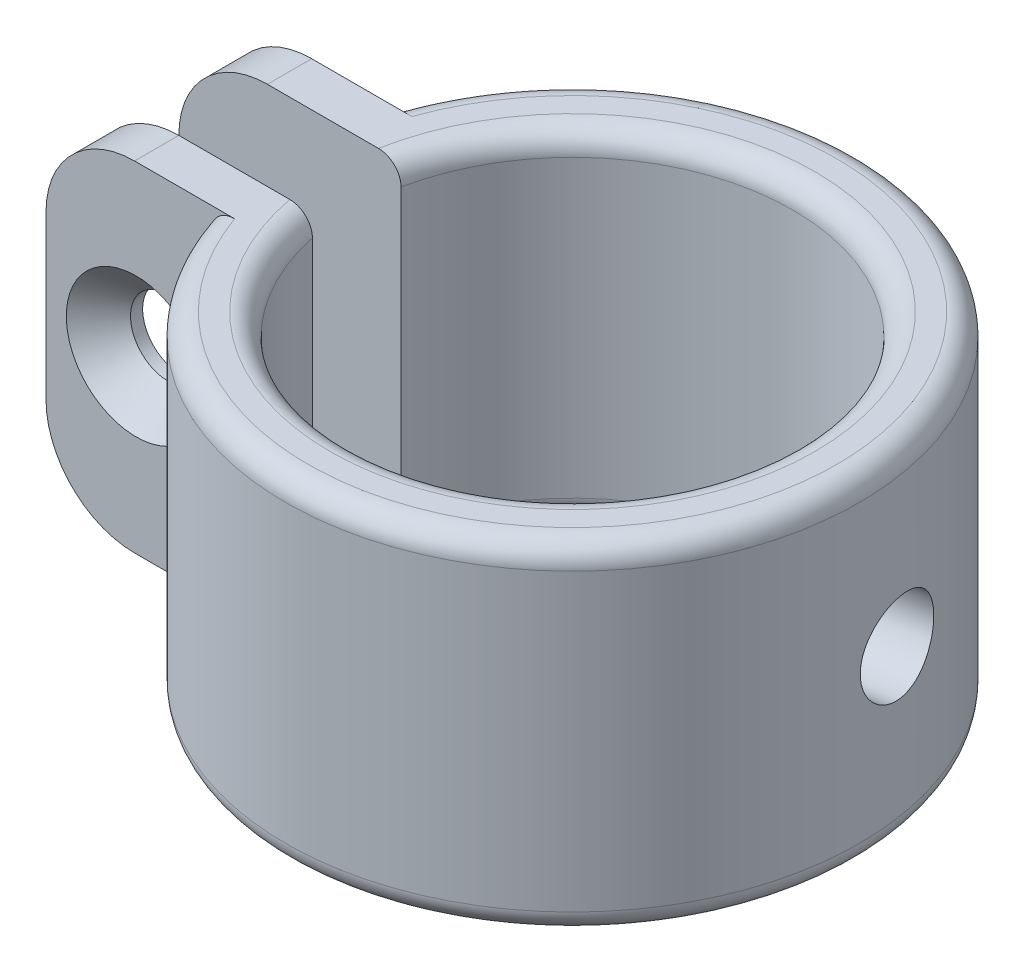
SolidWorks part; units mm, degrees
ref_plane "Front Plane" through (0, 0, 0) normal (0, 0, 1) x (1, 0, 0)
ref_plane "Top Plane" through (0, 0, 0) normal (0, 1, 0) x (1, 0, 0)
ref_plane "Right Plane" through (0, 0, 0) normal (1, 0, 0) x (0, 0, -1)
sketch "Sketch1" plane through (0, 0, 0) normal (0, 0, 1) x (1, 0, 0)
  line L0 (0, 0) -> (0, 130) construction
  line L1 (-9.95, 130) -> (9.95, 130) construction
  line L2 (-3.8, 7) -> (3.8, 7) construction
  line L3 (-3.8, 12.6) -> (3.8, 12.6) construction
  line L4 (-8.875, 30) -> (8.875, 30) construction
  line L5 (-7.05, 21) -> (7.05, 21) construction
  line L6 (-7.6, 30) -> (7.6, 30) construction
  line L7 (3.8, 7) -> (2.8, 7) construction
  line L8 (3.8, 7) -> (3.8, 12.6) construction
  line L9 (3.8, 12.6) -> (7.05, 21) construction
  line L10 (7.05, 21) -> (7.6, 30) construction
  line L11 (7.6, 30) -> (8.875, 30) construction
  line L12 (-9.95, 129.5) -> (9.95, 129.5) construction
  line L13 (8.875, 30) -> (9.95, 129.5) construction
  line L14 (9.95, 129.5) -> (9.95, 29.121) construction
  line L15 (9.95, 52.2759) -> (12.95, 52.2759)
  line L16 (9.95, 52.2759) -> (9.95, 36.9424)
  line L17 (9.95, 36.9424) -> (12.95, 36.9424)
  line L18 (12.95, 52.2759) -> (12.95, 36.9424)
  line L19 (9.95, 52.2759) -> (12.95, 36.9424) construction
  line L20 (9.95, 36.9424) -> (12.95, 52.2759) construction
  spline S0 degree 2 poles (0, 0) (0.935, 0.0329) (2.8, 7) knots 0 0 0 1 1 1 construction
  spline S1 degree 2 poles (0, 130) (7.4447, 130.0874) (9.95, 129.5) knots 0 0 0 1 1 1 construction
  point P4 (0, 130)
  point P7 (0, 7)
  point P10 (0, 12.6)
  point P13 (0, 30)
  point P16 (0, 21)
  point P20 (0, 30)
  point P23 (0, 129.5)
  point P24 (14.2691, 44.6124)
  point P26 (11.45, 44.6092)
  dimension "D1" = 130
  dimension "D2" = 19.9
  dimension "D3" = 30
  dimension "D4" = 7
  dimension "D5" = 5.6
  dimension "D6" = 9
  dimension "D7" = 17.75
  dimension "D8" = 7.6
  dimension "D9" = 14.1
  dimension "D10" = 15.2
  dimension "D11" = 1
  dimension "D12" = 0.5
  dimension "D13" = 3
revolve "Revolve1" add sketch "Sketch1" angle 360 about L0
fillet "Fillet1" radius 1 4 edges at (0, 36.9424, -9.95) (0, 36.9424, -12.95) (0, 52.2759, -12.95) (0, 52.2759, -9.95)
sketch "Sketch3" plane through (0, 0, 0) normal (0, 0, 1) x (1, 0, 0)
  line L1 (-14.4441, 52.4387) -> (-9.1794, 52.4387)
  line L2 (-14.4441, 52.4387) -> (-14.4441, 36.7797)
  line L3 (-14.4441, 36.7797) -> (-9.1794, 36.7797)
  line L4 (-9.1794, 52.4387) -> (-9.1794, 36.7797)
  line L5 (-14.4441, 52.4387) -> (-9.1794, 36.7797) construction
  line L6 (-14.4441, 36.7797) -> (-9.1794, 52.4387) construction
  point P0 (-11.8118, 44.6092)
  point P5 (-11.8118, 44.6092)
extrude "Cut-Extrude1" cut sketch "Sketch3" against normal mid plane 4
sketch "Sketch4" plane through (0, 0, 0) normal (0, 0, 1) x (1, 0, 0)
  line L0 (-10.7658, 36.9424) -> (-11.7814, 36.9424) construction
  line L1 (-12.7946, 37.9424) -> (-12.7946, 51.2759) construction
  line L2 (-11.7814, 52.2759) -> (-10.7658, 52.2759) construction
  line L3 (-9.7469, 51.2759) -> (-9.7469, 37.9424) construction
  line L4 (-10.7658, 36.9424) -> (-11.7814, 36.9424)
  line L5 (-12.7946, 37.9424) -> (-12.7946, 51.2759) construction
  line L6 (-11.7814, 52.2759) -> (-10.7658, 52.2759)
  line L7 (-9.7469, 51.2759) -> (-9.7469, 37.9424)
  line L9 (-11.7814, 36.9424) -> (-15.7814, 36.9424)
  line L10 (-11.7814, 36.9424) -> (-11.7814, 52.2759) construction
  line L11 (-11.7814, 52.2759) -> (-15.7814, 52.2759)
  line L12 (-19.7814, 40.9424) -> (-19.7814, 48.2759)
  arc A0 (-15.7814, 36.9424) -> (-19.7814, 40.9424) centre (-15.7814, 40.9424) cw
  arc A1 (-15.7814, 52.2759) -> (-19.7814, 48.2759) centre (-15.7814, 48.2759) ccw
  spline S0 degree 3 poles (-867.896, -1766.9535) (-94.3463, 89.6301) (-6.6797, 44.936) (-9.8775, 37.4356) (-9.9542, 37.3244) (-10.1426, 37.141) (-10.256, 37.0673) (-16.8792, 34.3862) (-57.0758, 97.7523) (1884.07, 674.2454) knots -14.959674 -14.959674 -14.959674 -14.959674 0.25 0.25 0.5 0.5 0.75 0.75 14.085045 14.085045 14.085045 14.085045 only from (-9.7469, 37.9424) to (-10.7658, 36.9424) construction
  spline S1 degree 3 poles (-1931.0915, 596.1355) (33.9921, 101.9114) (-5.5249, 34.3266) (-12.288, 37.0666) (-12.4019, 37.1408) (-12.5904, 37.326) (-12.6658, 37.437) (-15.5007, 44.1622) (53.9722, 84.2157) (597.3175, -1865.6992) knots -13.414243 -13.414243 -13.414243 -13.414243 0.25 0.25 0.5 0.5 0.75 0.75 14.388842 14.388842 14.388842 14.388842 only from (-11.7814, 36.9424) to (-12.7946, 37.9424) construction
  spline S2 degree 3 poles (530.6863, 1975.1274) (49.138, 6.4343) (-15.413, 45.2972) (-12.6646, 51.7836) (-12.5888, 51.8943) (-12.401, 52.078) (-12.2881, 52.1517) (-5.4959, 54.9039) (34.2919, -13.2346) (-1926.6386, -522.0043) knots -12.837209 -12.837209 -12.837209 -12.837209 0.25 0.25 0.5 0.5 0.75 0.75 14.477367 14.477367 14.477367 14.477367 only from (-12.7946, 51.2759) to (-11.7814, 52.2759) construction
  spline S3 degree 3 poles (1739.372, -912.897) (-89.6226, -11.6565) (-15.8855, 57.6651) (-9.9537, 51.8934) (-9.8775, 51.7825) (-7.0249, 45.0906) (-76.1769, 4.8347) (-645.7304, 1946.4585) knots -14.873424 -14.873424 -14.873424 -14.873424 0.5 0.5 0.75 0.75 14.300264 14.300264 14.300264 14.300264 only from (-10.7658, 52.2759) to (-9.7469, 51.2759) construction
  spline S4 degree 3 poles (-9.7469, 37.9424) (-9.7469, 37.8096) (-9.7741, 37.6782) (-9.8775, 37.4356) (-9.9542, 37.3244) (-10.1426, 37.141) (-10.256, 37.0673) (-10.4998, 36.9686) (-10.6335, 36.9424) (-10.7658, 36.9424) knots 0 0 0 0 0.25 0.25 0.5 0.5 0.75 0.75 1 1 1 1
  spline S5 degree 3 poles (-11.7814, 36.9424) (-11.9125, 36.9424) (-12.045, 36.9681) (-12.288, 37.0666) (-12.4019, 37.1408) (-12.5904, 37.326) (-12.6658, 37.437) (-12.7679, 37.6791) (-12.7946, 37.8114) (-12.7946, 37.9424) knots 0 0 0 0 0.25 0.25 0.5 0.5 0.75 0.75 1 1 1 1 construction
  spline S6 degree 3 poles (-12.7946, 51.2759) (-12.7946, 51.407) (-12.7677, 51.5404) (-12.6646, 51.7836) (-12.5888, 51.8943) (-12.401, 52.078) (-12.2881, 52.1517) (-12.0451, 52.2501) (-11.9126, 52.2759) (-11.7814, 52.2759) knots 0 0 0 0 0.25 0.25 0.5 0.5 0.75 0.75 1 1 1 1 construction
  spline S7 degree 3 poles (-10.7658, 52.2759) (-10.5001, 52.2759) (-10.2385, 52.1705) (-9.9537, 51.8934) (-9.8775, 51.7825) (-9.7741, 51.5401) (-9.7469, 51.4074) (-9.7469, 51.2759) knots 0 0 0 0 0.5 0.5 0.75 0.75 1 1 1 1
  point P14 (-19.7814, 52.2759)
  dimension "D2" = 4
  dimension "D1" = 8
extrude "Boss-Extrude1" add sketch "Sketch4" against normal blind 2 from offset 2 contours A0 L12 A1 L11 L6 S7 L7 S4 L4 L9 offset against normal yes
mirror "Mirror1" about plane through (0, 0, 0) normal (0, 0, 1) of "Boss-Extrude1"
hole_wizard "CSK for M3 Flat Head Machine Screw1" positions "Sketch5" profile "Sketch6" countersink size "M3" standard "ANSI Metric"
sketch "Sketch5" plane through (0, 0, 4) normal (0, 0, 1) x (1, 0, 0)
  point P0 (-15.7153, 44.6668)
  point P3 (-15.7153, 44.6668)
  point P6 (-15.3815, 44.632)
  point P7 (0, 0)
  point P8 (-15.7153, 44.6668)
sketch "Sketch6" plane through (-15.7153, 44.6668, 4) normal (1, 0, 0) x (0, -1, 0)
  line L0 (0, 0) -> (0, 11.0715)
  line L1 (0, 11.0715) -> (1.7, 10.05)
  line L2 (1.7, 10.05) -> (1.7, 1.45)
  line L3 (1.7, 1.45) -> (3.15, 0)
  line L5 (3.15, 0) -> (0, 0)
  line L6 (-1.7, 1.45) -> (-3.15, 0) construction
  line L10 (0, 11.0715) -> (-1.7, 10.05) construction
  line L11 (0, -6.35) -> (0, 107.95) construction
  dimension "Hole Dia." = 3.4
  dimension "Hole Depth" = 10.05
  dimension "Near C'Sink Dia." = 6.3
  dimension "Near C'Sink Angle" = 90
  dimension "Drill Angle" = 118
sketch "Sketch7" plane through (0, 0, -4) normal (0, 0, -1) x (-1, 0, 0)
  line L1 (15.7153, 47.9) -> (12.9153, 46.2834)
  line L2 (12.9153, 46.2834) -> (12.9153, 43.0502)
  line L3 (12.9153, 43.0502) -> (15.7153, 41.4337)
  line L4 (15.7153, 41.4337) -> (18.5153, 43.0502)
  line L5 (18.5153, 43.0502) -> (18.5153, 46.2834)
  line L6 (18.5153, 46.2834) -> (15.7153, 47.9)
  circle A0 centre (15.7153, 44.6668) radius 2.8 construction
  dimension "D1" = 5.6
extrude "Cut-Extrude2" cut sketch "Sketch7" against normal blind 1
sketch "Sketch8" plane through (0, 0, -2) normal (0, 0, 1) x (1, 0, 0)
  line L0 (12.95, 51.2759) -> (12.95, 37.9424) construction
  point P4 (12.95, 44.6092)
  point P5 (0, 0)
  point P6 (0, 0)
  point P7 (0, 0)
ref_point "Point1"
hole_wizard "Ø4.0mm Dowel Hole1" positions "3DSketch1" profile "Sketch2" hole size "Ø4.0" standard "ANSI Metric"
sketch3d "3DSketch1"
  point P0 (12.7874, 44.5408, -2.0457)
  point P24 (12.8975, 45.3759, -1.165)
  point P25 (12.95, 44.6092, -2)
sketch "Sketch2" plane through (12.7874, 44.5408, -2.0457) normal (0, 1, 0) x (-0.158, 0, -0.9874)
  line L0 (0, 0) -> (0, 11.2517)
  line L1 (0, 11.2517) -> (2, 10.05)
  line L2 (2, 10.05) -> (2, 0)
  line L5 (2, 0) -> (0, 0)
  line L10 (0, 11.2517) -> (-2, 10.05) construction
  line L11 (0, -6.35) -> (0, 107.95) construction
  dimension "Hole Dia." = 4
  dimension "Hole Depth" = 10.05
  dimension "Drill Angle" = 118
